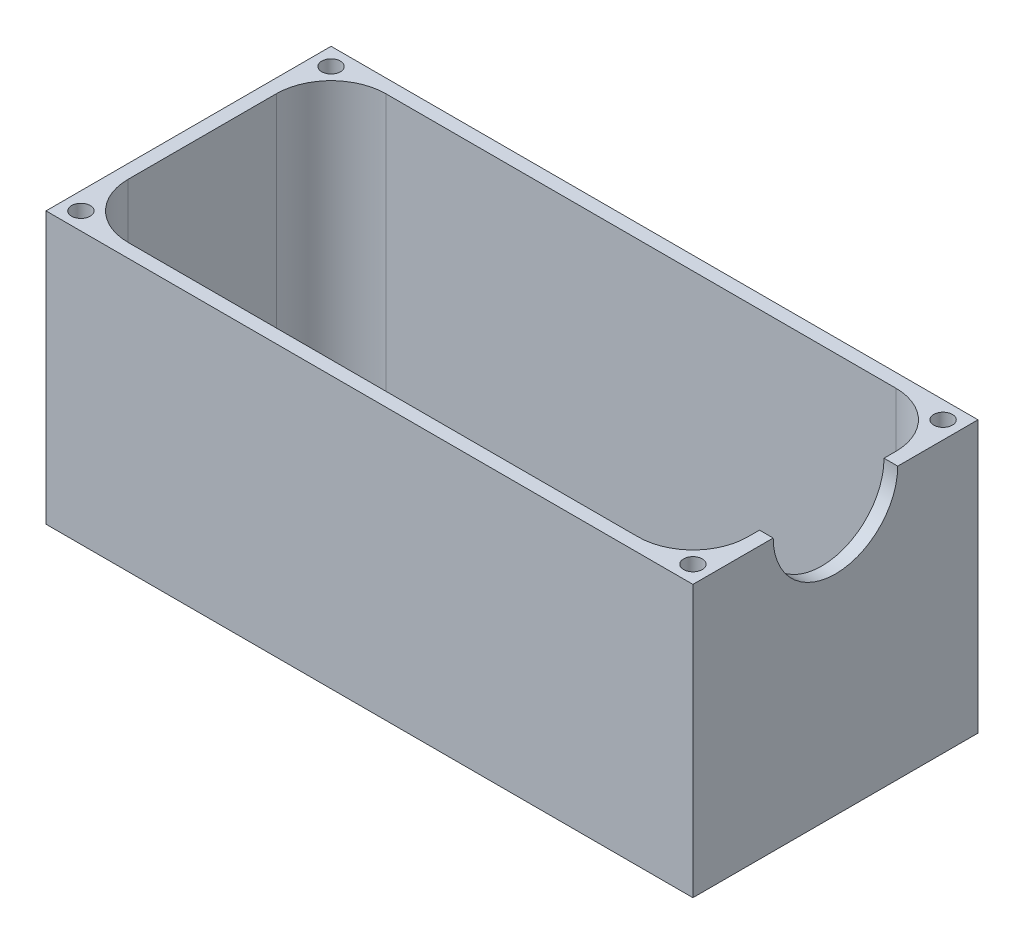
SolidWorks part; units mm, degrees
ref_plane "Front Plane" through (0, 0, 0) normal (0, 0, 1) x (1, 0, 0)
ref_plane "Top Plane" through (0, 0, 0) normal (0, 1, 0) x (1, 0, 0)
ref_plane "Right Plane" through (0, 0, 0) normal (1, 0, 0) x (0, 0, -1)
sketch "Sketch1" plane through (0, 0, 0) normal (0, 1, 0) x (1, 0, 0)
  line L1 (-52.1066, 32.5272) -> (65.8934, 32.5272)
  line L2 (-52.1066, 32.5272) -> (-52.1066, -19.4728)
  line L3 (-52.1066, -19.4728) -> (65.8934, -19.4728)
  line L4 (65.8934, 32.5272) -> (65.8934, -19.4728)
extrude "Boss-Extrude1" add sketch "Sketch1" along normal blind 2.5
sketch "Sketch2" plane through (0, 2.5, 0) normal (0, 1, 0) x (1, 0, 0)
  line L1 (-52.1066, 32.5272) -> (65.8934, 32.5272)
  line L2 (-52.1066, 32.5272) -> (-52.1066, -19.4728)
  line L3 (-52.1066, -19.4728) -> (65.8934, -19.4728)
  line L4 (65.8934, 32.5272) -> (65.8934, -19.4728)
extrude "Extrude-Thin1" add sketch "Sketch2" along normal blind 47 thin
fillet "Fillet1" radius 10 4 edges at (63.3934, 26, 16.9728) (63.3934, 26, -30.0272) (-49.6066, 26, -30.0272) (-49.6066, 26, 16.9728)
sketch "Sketch3" plane through (65.8934, 0, 0) normal (1, 0, 0) x (0, 0, -1)
  line L0 (-19.4728, 49.5) -> (32.5272, 49.5) construction
  line L1 (-4.8319, 49.5) -> (17.8863, 49.5)
  arc A0 (17.8863, 49.5) -> (-4.8319, 49.5) centre (6.5272, 49.5) cw
extrude "Cut-Extrude1" cut sketch "Sketch3" against normal blind 42.5
sketch "Sketch4" plane through (0, 0, 0) normal (0, 0, 1) x (1, 0, 0)
  line L0 (-19.8209, -132.0415) -> (-16.6389, -128.8595)
  line L1 (-19.8209, -80.0415) -> (98.1791, -80.0415)
  line L2 (-19.8209, -80.0415) -> (-19.8209, -132.0415)
  line L3 (-19.8209, -132.0415) -> (98.1791, -132.0415)
  line L4 (98.1791, -80.0415) -> (98.1791, -132.0415)
  line L5 (39.1791, -82.5415) -> (39.1791, -129.5415)
  line L8 (98.1791, -132.0415) -> (94.9971, -128.8595)
  line L9 (-17.3209, -106.0415) -> (98.1791, -106.0415)
  line L11 (98.1791, -80.0415) -> (94.9971, -83.2235)
  line L12 (-19.8209, -80.0415) -> (-16.6389, -83.2235)
  circle A0 centre (-16.6389, -128.8595) radius 2
  circle A1 centre (94.9971, -128.8595) radius 2
  circle A2 centre (94.9971, -83.2235) radius 2
  circle A3 centre (-16.6389, -83.2235) radius 2
sketch "Sketch5" plane through (0, 49.5, 0) normal (0, 1, 0) x (1, 0, 0)
  line L0 (-52.1066, -19.4728) -> (-48.9246, -16.2909)
  line L1 (-49.6066, 6.5272) -> (66.3852, 6.5272)
  line L2 (-49.6066, 20.0272) -> (-49.6066, -6.9728) construction
  line L3 (6.8934, 30.0272) -> (6.8934, -16.9728)
  line L4 (53.3934, 30.0272) -> (-39.6066, 30.0272) construction
  line L5 (-39.6066, -16.9728) -> (53.3934, -16.9728) construction
  line L6 (-52.1066, 32.5272) -> (-48.9246, 29.3452)
  line L7 (65.8934, -19.4728) -> (62.7114, -16.2909)
  line L8 (65.8934, 32.5272) -> (62.7114, 29.3452)
  circle A0 centre (-48.9246, -16.2909) radius 1.7
  circle A1 centre (-48.9246, 29.3452) radius 1.7
  circle A2 centre (62.7114, -16.2909) radius 1.7
  circle A3 centre (62.7114, 29.3452) radius 1.7
extrude "Cut-Extrude2" cut sketch "Sketch5" against normal blind 6 contours A0 | A1 | A3 | A2
